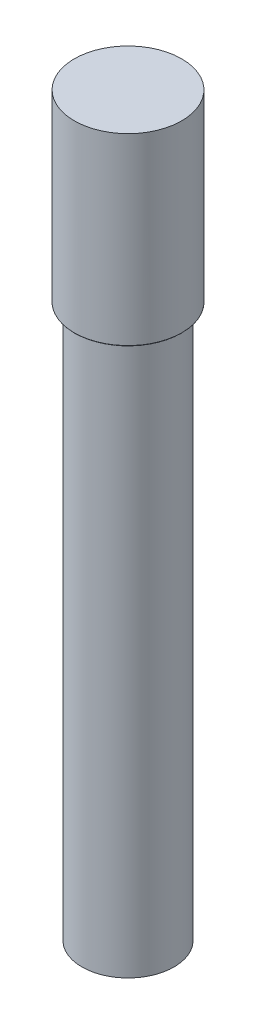
SolidWorks part; units mm, degrees
ref_plane "Front Plane" through (0, 0, 0) normal (0, 0, 1) x (1, 0, 0)
ref_plane "Top Plane" through (0, 0, 0) normal (0, 1, 0) x (1, 0, 0)
ref_plane "Right Plane" through (0, 0, 0) normal (1, 0, 0) x (0, 0, -1)
sketch "Sketch2" plane through (0, 0, 0) normal (0, 1, 0) x (1, 0, 0)
  circle A0 centre (0, 0) radius 19.05
  dimension "D1" = 38.1
extrude "Boss-Extrude1" add sketch "Sketch2" along normal blind 228.6
sketch "Sketch3" plane through (0, 228.6, 0) normal (0, 1, 0) x (1, 0, 0)
  circle A0 centre (0, 0) radius 22.225
  dimension "D1" = 44.45
extrude "Boss-Extrude2" add sketch "Sketch3" along normal blind 76.2
fillet "Fillet1" radius 0.254 2 edges at (0, 228.6, 19.05) (0, 228.6, 22.225)
